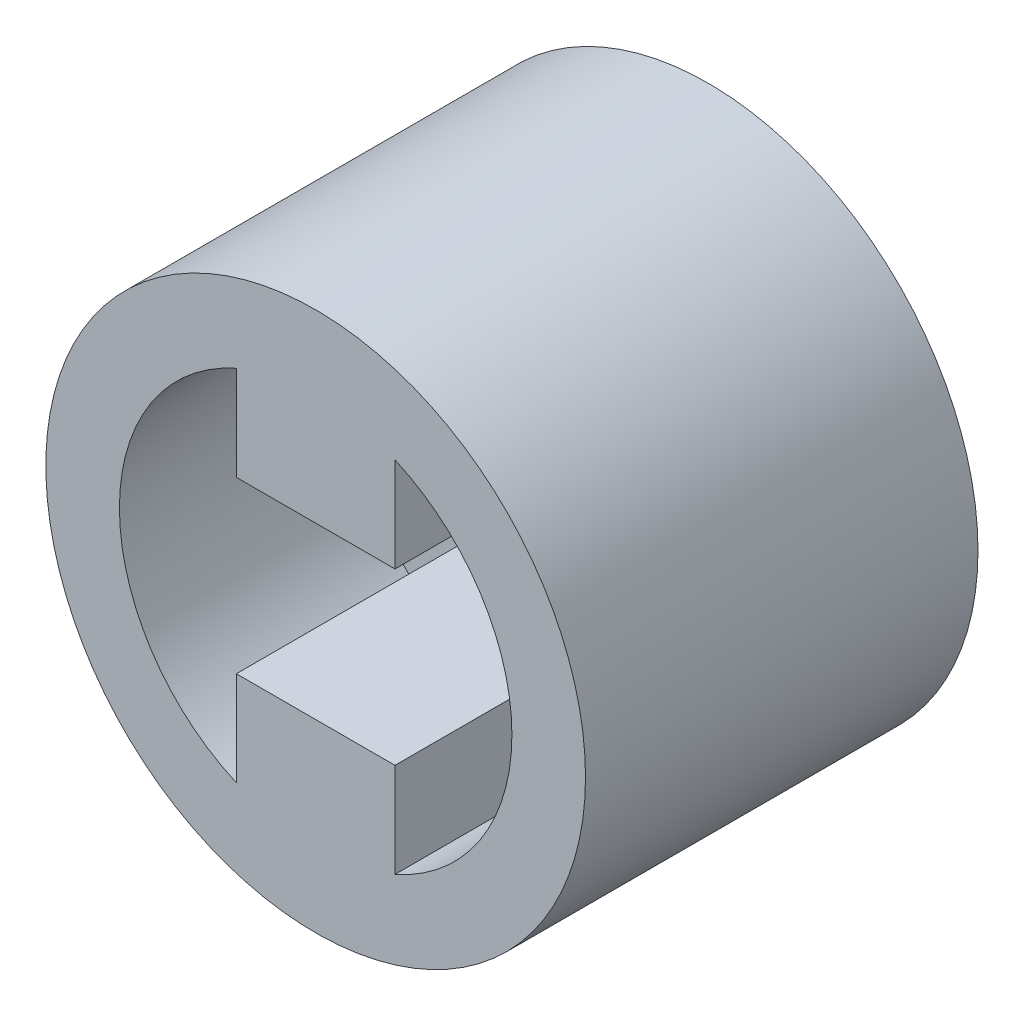
SolidWorks part; units mm, degrees
ref_plane "Front Plane" through (0, 0, 0) normal (0, 0, 1) x (1, 0, 0)
ref_plane "Top Plane" through (0, 0, 0) normal (0, 1, 0) x (1, 0, 0)
ref_plane "Right Plane" through (0, 0, 0) normal (1, 0, 0) x (0, 0, -1)
sketch "Sketch1" plane through (0, 0, 0) normal (0, 0, 1) x (1, 0, 0)
  circle A0 centre (0, 0) radius 8.25
  dimension "D1" = 16.5
extrude "Boss-Extrude1" add sketch "Sketch1" along normal blind 12
sketch "Sketch2" plane through (0, 0, 12) normal (0, 0, 1) x (1, 0, 0)
  line L1 (-2.425, 9.4) -> (2.425, 9.4)
  line L2 (-2.425, 9.4) -> (-2.425, 2.6)
  line L3 (-2.425, 2.6) -> (2.425, 2.6)
  line L4 (2.425, 9.4) -> (2.425, 2.6)
  line L5 (-2.425, 9.4) -> (2.425, 2.6) construction
  line L6 (-2.425, 2.6) -> (2.425, 9.4) construction
  line L7 (-2.425, -2.6) -> (2.425, -2.6)
  line L8 (-2.425, -2.6) -> (-2.425, -9.4)
  line L9 (-2.425, -9.4) -> (2.425, -9.4)
  line L10 (2.425, -2.6) -> (2.425, -9.4)
  line L11 (-2.425, -2.6) -> (2.425, -9.4) construction
  line L12 (-2.425, -9.4) -> (2.425, -2.6) construction
  circle A0 centre (0, 0) radius 6
  point P3 (0, 6)
  point P8 (0, -6)
  dimension "D1" = 12
  dimension "D2" = 4.85
  dimension "D3" = 4.85
  dimension "D4" = 3.4
  dimension "D5" = 3.4
extrude "Cut-Extrude1" cut sketch "Sketch2" against normal blind 7 contours L2 A0 L8 L7 L10 L4 L3
sketch "Sketch3" plane through (0, 0, 0) normal (0, 0, -1) x (-1, 0, 0)
  line L1 (2.3094, 0) -> (1.1547, 2)
  line L2 (1.1547, 2) -> (-1.1547, 2)
  line L3 (-1.1547, 2) -> (-2.3094, 0)
  line L4 (-2.3094, 0) -> (-1.1547, -2)
  line L5 (-1.1547, -2) -> (1.1547, -2)
  line L6 (1.1547, -2) -> (2.3094, 0)
  circle A0 centre (0, 0) radius 2 construction
  dimension "D1" = 4
extrude "Cut-Extrude2" cut sketch "Sketch3" against normal through all
equation "\"D3@Sketch2\"=\"D2@Sketch2\""
